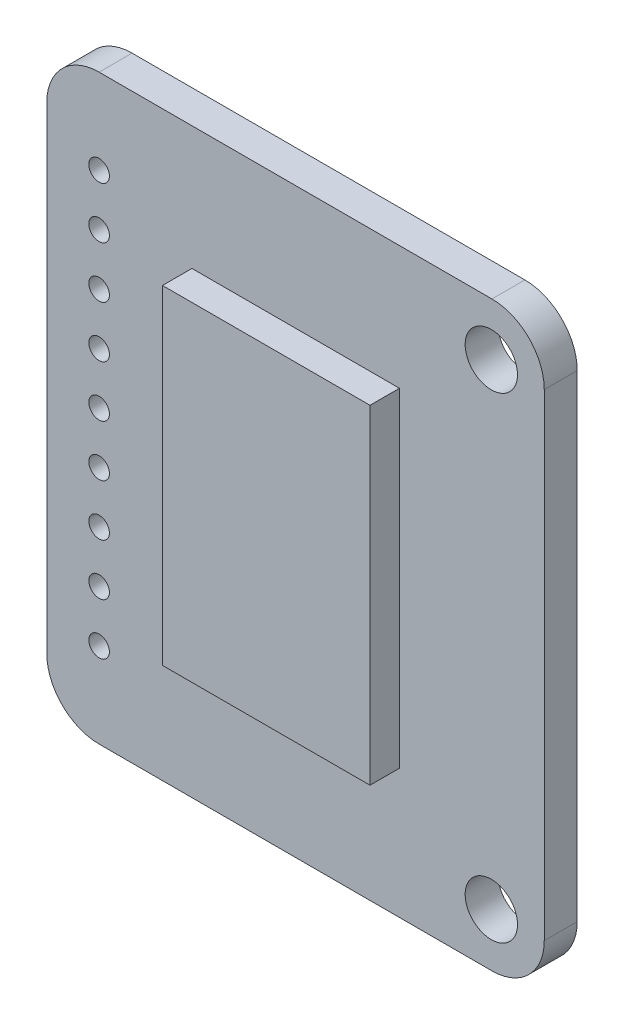
SolidWorks part; units mm, degrees
ref_plane "Front Plane" through (0, 0, 0) normal (0, 0, 1) x (1, 0, 0)
ref_plane "Top Plane" through (0, 0, 0) normal (0, 1, 0) x (1, 0, 0)
ref_plane "Right Plane" through (0, 0, 0) normal (1, 0, 0) x (0, 0, -1)
sketch "Sketch1" plane through (0, 0, 0) normal (0, 0, 1) x (1, 0, 0)
  line L1 (-12.075, -14.125) -> (12.075, -14.125)
  line L2 (-12.075, -14.125) -> (-12.075, 14.125)
  line L3 (-12.075, 14.125) -> (12.075, 14.125)
  line L4 (12.075, -14.125) -> (12.075, 14.125)
  line L5 (-12.075, -14.125) -> (12.075, 14.125) construction
  line L6 (-12.075, 14.125) -> (12.075, -14.125) construction
  point P0 (0, 0)
  dimension "D1" = 28.25
  dimension "D2" = 24.15
extrude "Boss-Extrude1" add sketch "Sketch1" along normal blind 1.6
sketch "Sketch2" plane through (0, 0, 1.6) normal (0, 0, 1) x (1, 0, 0)
  line L3 (9.505, 11.557) -> (9.505, -11.557) construction
  line L5 (12.075, -14.125) -> (12.075, 14.125) construction
  circle A0 centre (9.505, 11.557) radius 1.27
  circle A1 centre (9.505, -11.557) radius 1.27
  point P4 (9.505, 0)
  dimension "D1" = 23.114
  dimension "D2" = 2.54
  dimension "D3" = 2.57
extrude "Cut-Extrude1" cut sketch "Sketch2" against normal through all
fillet "Fillet1" radius 2.54 4 edges at (-12.075, 14.125, 0.8) (-12.075, -14.125, 0.8) (12.075, -14.125, 0.8) (12.075, 14.125, 0.8)
sketch "Sketch3" plane through (0, 0, 1.6) normal (0, 0, 1) x (1, 0, 0)
  line L0 (-12.075, 11.585) -> (-12.075, -11.585) construction
  circle A0 centre (-9.535, 0) radius 0.5
  dimension "D1" = 1
  dimension "D2" = 2.54
extrude "Cut-Extrude2" cut sketch "Sketch3" against normal through all
pattern_linear "LPattern1" count 5 spacing 2.5 along (0, -1, 0) count 5 spacing 2.5 along (0, 1, 0) of "Cut-Extrude2"
sketch "Sketch4" plane through (0, 0, 1.6) normal (0, 0, 1) x (1, 0, 0)
  line L1 (-5.0281, 8.1252) -> (5.0456, 8.1252)
  line L2 (-5.0281, 8.1252) -> (-5.0281, -7.8488)
  line L3 (-5.0281, -7.8488) -> (5.0456, -7.8488)
  line L4 (5.0456, 8.1252) -> (5.0456, -7.8488)
extrude "Boss-Extrude2" add sketch "Sketch4" along normal blind 1.43
